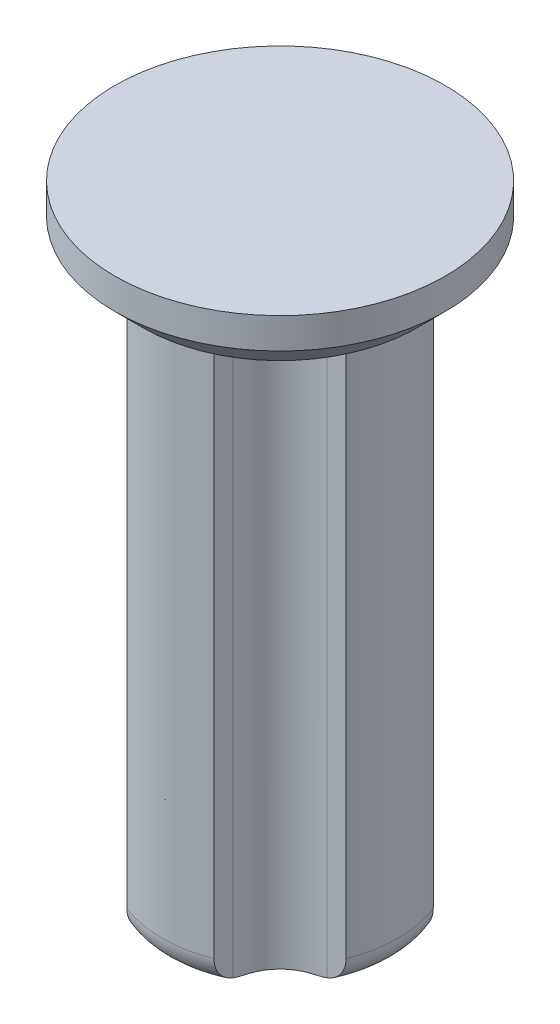
SolidWorks part; units mm, degrees
ref_plane "Front Plane" through (0, 0, 0) normal (0, 0, 1) x (1, 0, 0)
ref_plane "Top Plane" through (0, 0, 0) normal (0, 1, 0) x (1, 0, 0)
ref_plane "Right Plane" through (0, 0, 0) normal (1, 0, 0) x (0, 0, -1)
sketch "Sketch1" plane through (0, 0, 0) normal (0, 1, 0) x (1, 0, 0)
  circle A0 centre (0, 0) radius 2.2225
  dimension "D1" = 4.445
extrude "Boss-Extrude1" add sketch "Sketch1" along normal blind 0.7937
sketch "Sketch2" plane through (0, 0, 0) normal (0, -1, 0) x (1, 0, 0)
  circle A0 centre (0, 0) radius 1.5875
  dimension "D1" = 3.175
extrude "Boss-Extrude2" add sketch "Sketch2" along normal blind 7.62
sketch "Sketch3" plane through (0, -7.62, 0) normal (0, -1, 0) x (1, 0, 0)
  line L0 (-0.5863, 1.4753) -> (-0.5863, 0.5863)
  line L1 (-0.5863, 0.5863) -> (-1.4753, 0.5863)
  line L2 (-1.4753, -0.5863) -> (-0.5863, -0.5863)
  line L3 (-0.5863, -0.5863) -> (-0.5863, -1.4753)
  line L4 (0.5863, 1.4753) -> (0.5863, 0.5863)
  line L5 (0.5863, 0.5863) -> (1.4753, 0.5863)
  line L6 (0.5863, -1.4753) -> (0.5863, -0.5863)
  line L7 (0.5863, -0.5863) -> (1.4753, -0.5863)
  circle A0 centre (0, 0) radius 1.5875 construction
  arc A1 (-1.4753, -0.5863) -> (-0.5863, -1.4753) centre (0, 0) ccw
  arc A2 (1.4753, 0.5863) -> (0.5863, 1.4753) centre (0, 0) ccw
  arc A3 (-0.5863, 1.4753) -> (-1.4753, 0.5863) centre (0, 0) ccw
  arc A4 (0.5863, -1.4753) -> (1.4753, -0.5863) centre (0, 0) ccw
  dimension "D1" = 0.889
extrude "Cut-Extrude2" cut sketch "Sketch3" against normal up to surface (7.62 mm away) up to face at (0, 0, -1.5875)
fillet "Fillet1" radius 0.635 4 edges at (-0.5863, -3.81, -0.5863) (0.5863, -3.81, -0.5863) (0.5863, -3.81, 0.5863) (-0.5863, -3.81, 0.5863)
fillet "Fillet2" radius 0.381 4 edges at (-1.5875, -7.62, 0) (0, -7.62, -1.5875) (1.5875, -7.62, 0) (0, -7.62, 1.5875)
chamfer "Chamfer1" distance 0.381 angle 45 1 edges at (0, 0, 2.2225)
